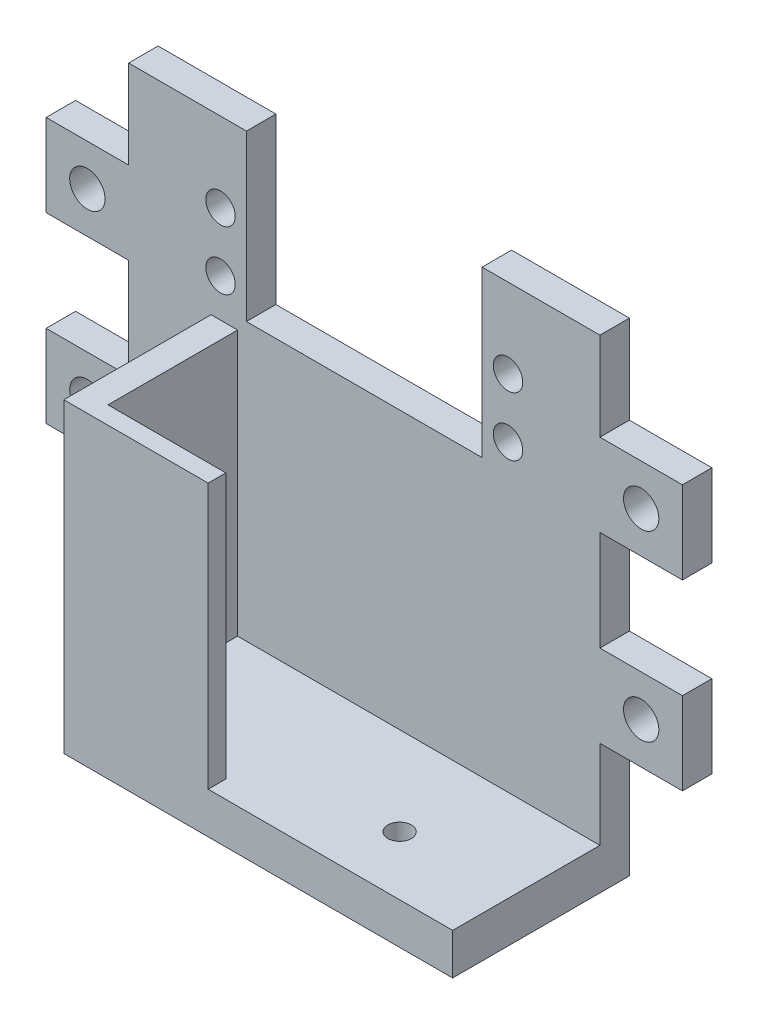
SolidWorks part; units mm, degrees
ref_plane "Plan de face" through (0, 0, 0) normal (0, 0, 1) x (1, 0, 0)
ref_plane "Plan de dessus" through (0, 0, 0) normal (0, 1, 0) x (1, 0, 0)
ref_plane "Plan de droite" through (0, 0, 0) normal (1, 0, 0) x (0, 0, -1)
sketch "Esquisse1" plane through (0, 0, 0) normal (0, 0, 1) x (1, 0, 0)
  line L0 (20, 47) -> (60, 47)
  line L1 (60, 47) -> (60, 66)
  line L2 (60, 66) -> (20, 66)
  line L3 (20, 66) -> (20, 47)
  line L4 (0, 75) -> (0, 0)
  line L5 (0, 0) -> (80, 0)
  line L6 (80, 0) -> (80, 75)
  line L7 (80, 75) -> (0, 75)
  line L8 (80, 60) -> (94, 60)
  line L9 (94, 60) -> (94, 46)
  line L10 (94, 46) -> (80, 46)
  line L11 (0, 37.5) -> (80, 37.5) construction
  line L12 (40, 75) -> (40, 0) construction
  line L13 (-14, 46) -> (0, 46)
  line L14 (-14, 60) -> (-14, 46)
  line L15 (0, 60) -> (-14, 60)
  line L16 (94, 29) -> (80, 29)
  line L17 (94, 15) -> (94, 29)
  line L18 (80, 15) -> (94, 15)
  line L19 (0, 15) -> (-14, 15)
  line L20 (-14, 29) -> (0, 29)
  line L21 (-14, 15) -> (-14, 29)
  dimension "D1" = 40
  dimension "D2" = 19
  dimension "D3" = 20
  dimension "D4" = 80
  dimension "D5" = 9
  dimension "D6" = 75
  dimension "D7" = 15
  dimension "D8" = 14
  dimension "D9" = 14
extrude "Boss.-Extru.1" add sketch "Esquisse1" along normal blind 5 contours L6 L7 L4 L5 L3 L2 L1 L0 | L4 L15 L14 L13 | L21 L19 L4 L20 | L10 L9 L8 L6 | L6 L18 L17 L16
sketch "Esquisse2" plane through (0, 0, 5) normal (0, 0, 1) x (1, 0, 0)
  line L0 (40, 75) -> (40, 0) construction
  line L1 (80, 75) -> (0, 75) construction
  line L2 (0, 0) -> (80, 0) construction
  line L3 (0, 37.5) -> (80, 37.5) construction
  line L4 (0, 46) -> (0, 29) construction
  line L5 (80, 29) -> (80, 46) construction
  circle A0 centre (-7, 53) radius 3
  circle A1 centre (-7, 22) radius 3
  circle A2 centre (87, 22) radius 3
  circle A3 centre (87, 53) radius 3
  dimension "D1" = 6
  dimension "D2" = 7
  dimension "D3" = 7
extrude "Enlèv. mat.-Extru.1" cut sketch "Esquisse2" against normal up to next
sketch "Esquisse3" plane through (0, 0, 0) normal (0, 0, 1) x (1, 0, 0)
  line L0 (80, 0) -> (80, -7)
  line L1 (80, -7) -> (0, -7)
  line L2 (0, -7) -> (0, 0)
  line L3 (0, 0) -> (80, 0)
  line L23 (80, 0) -> (80, 15)
  line L24 (80, 15) -> (94, 15)
  line L25 (94, 15) -> (94, 29)
  line L26 (94, 29) -> (80, 29)
  line L27 (80, 29) -> (80, 46)
  line L28 (80, 46) -> (94, 46)
  line L29 (94, 46) -> (94, 60)
  line L30 (94, 60) -> (80, 60)
  line L31 (80, 60) -> (80, 75)
  line L32 (80, 75) -> (0, 75)
  line L33 (0, 75) -> (0, 60)
  line L34 (0, 60) -> (-14, 60)
  line L35 (-14, 60) -> (-14, 46)
  line L36 (-14, 46) -> (0, 46)
  line L37 (0, 46) -> (0, 29)
  line L38 (0, 29) -> (-14, 29)
  line L39 (-14, 29) -> (-14, 15)
  line L40 (-14, 15) -> (0, 15)
  line L41 (0, 15) -> (0, 0)
  line L42 (0, 0) -> (80, 0)
  line L43 (80, 0) -> (80, 15)
  line L44 (80, 15) -> (94, 15)
  line L45 (94, 15) -> (94, 29)
  line L46 (94, 29) -> (80, 29)
  line L47 (80, 29) -> (80, 46)
  line L48 (80, 46) -> (94, 46)
  line L49 (94, 46) -> (94, 60)
  line L50 (94, 60) -> (80, 60)
  line L51 (80, 60) -> (80, 75)
  line L52 (80, 75) -> (0, 75)
  line L53 (0, 75) -> (0, 60)
  line L54 (0, 60) -> (-14, 60)
  line L55 (-14, 60) -> (-14, 46)
  line L56 (-14, 46) -> (0, 46)
  line L57 (0, 46) -> (0, 29)
  line L58 (0, 29) -> (-14, 29)
  line L59 (-14, 29) -> (-14, 15)
  line L60 (-14, 15) -> (0, 15)
  line L61 (0, 15) -> (0, 0)
  dimension "D1" = 7
  dimension "D2" = 0
extrude "Boss.-Extru.2" add sketch "Esquisse3" along normal blind 30 contours L3 L2 L1 L0
sketch "Esquisse4" plane through (0, 0, 0) normal (0, 0, -1) x (-1, 0, 0)
  line L0 (-60, 66) -> (-67, 66) construction
  line L1 (-60, 47) -> (-67, 47) construction
  line L2 (-67, 47) -> (-67, 66) construction
  line L3 (-20, 66) -> (-13, 66) construction
  line L4 (-13, 66) -> (-13, 47) construction
  line L5 (-13, 47) -> (-20, 47) construction
  line L6 (-40, 66) -> (-40, 47) construction
  line L7 (-60, 66) -> (-20, 66) construction
  line L8 (-20, 47) -> (-60, 47) construction
  line L9 (-67, 56.5) -> (-13, 56.5) construction
  circle A0 centre (-64.4, 61.5) radius 2.5
  circle A1 centre (-15.6, 61.5) radius 2.5
  circle A2 centre (-15.6, 51.5) radius 2.5
  circle A3 centre (-64.4, 51.5) radius 2.5
  dimension "D3" = 5
  dimension "D1" = 4.5
  dimension "D2" = 2.6
  dimension "D4" = 7
extrude "Enlèv. mat.-Extru.2" cut sketch "Esquisse4" against normal up to next
sketch "Esquisse5" plane through (0, 0, 0) normal (0, 0, -1) x (-1, 0, 0)
  line L0 (-60, 66) -> (-60, 75)
  line L1 (-80, 75) -> (0, 75) construction
  line L2 (-60, 66) -> (-20, 66)
  line L3 (-20, 66) -> (-20, 75)
  line L4 (-20, 75) -> (-60, 75)
extrude "Enlèv. mat.-Extru.3" cut sketch "Esquisse5" against normal up to next
sketch "Esquisse6" plane through (0, 0, 0) normal (0, 1, 0) x (1, 0, 0)
  circle A0 centre (61, -20) radius 2
  dimension "D1" = 4
  dimension "D2" = 19
  dimension "D3" = 15
extrude "Enlèv. mat.-Extru.4" cut sketch "Esquisse6" against normal blind 4
sketch "Esquisse7" plane through (0, 0, 5) normal (0, 0, 1) x (1, 0, 0)
  line L0 (18.5, 45) -> (18.5, 0)
  line L1 (0, 0) -> (80, 0) construction
  line L2 (18.5, 0) -> (14, 0)
  line L3 (0, 0) -> (80, 0) construction
  line L4 (14, 0) -> (14, 45)
  line L5 (14, 45) -> (18.5, 45)
  dimension "D1" = 45
  dimension "D2" = 4.5
  dimension "D3" = 1.5
extrude "Boss.-Extru.3" add sketch "Esquisse7" along normal blind 25
sketch "Esquisse8" plane through (18.5, 0, 0) normal (1, 0, 0) x (0, 0, -1)
  line L0 (-27, 45) -> (-27, 0)
  line L1 (-30, 45) -> (-5, 45) construction
  line L2 (-30, 0) -> (-5, 0) construction
  line L3 (-27, 0) -> (-30, 0)
  line L4 (-30, 0) -> (-30, 45)
  line L5 (-30, 45) -> (-27, 45)
  dimension "D1" = 3
extrude "Boss.-Extru.4" add sketch "Esquisse8" along normal blind 20
sketch "Esquisse9" plane through (0, 0, 5) normal (0, 0, 1) x (1, 0, 0)
  line L0 (0, 15) -> (14, 15)
  line L1 (14, 45) -> (14, 0) construction
  line L2 (14, 15) -> (14, 0)
  line L3 (14, 0) -> (0, 0)
  line L4 (0, 0) -> (0, 15)
extrude "Enlèv. mat.-Extru.5" cut sketch "Esquisse9" against normal up to next
sketch "Esquisse11" plane through (0, 0, 30) normal (0, 0, 1) x (1, 0, 0)
  line L0 (0, 0) -> (14, 0)
  line L1 (14, 0) -> (14, -7)
  line L2 (80, -7) -> (0, -7) construction
  line L3 (14, -7) -> (0, -7)
  line L4 (0, -7) -> (0, 0)
extrude "Enlèv. mat.-Extru.9" cut sketch "Esquisse11" against normal up to next
